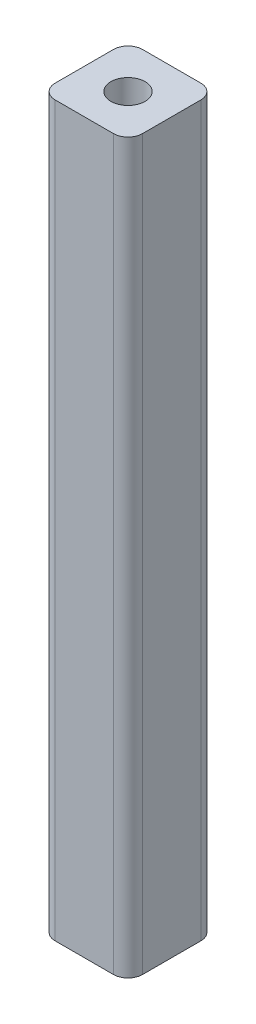
SolidWorks part; units mm, degrees
ref_plane "Front Plane" through (0, 0, 0) normal (0, 0, 1) x (1, 0, 0)
ref_plane "Top Plane" through (0, 0, 0) normal (0, 1, 0) x (1, 0, 0)
ref_plane "Right Plane" through (0, 0, 0) normal (1, 0, 0) x (0, 0, -1)
sketch "Sketch1" plane through (0, 0, 0) normal (0, 1, 0) x (1, 0, 0)
  line L0 (-6, 6) -> (6, -6) construction
  line L1 (-6, 6) -> (6, 6)
  line L2 (-6, 6) -> (-6, -6)
  line L3 (-6, -6) -> (6, -6)
  line L4 (6, 6) -> (6, -6)
  circle A0 centre (0, 0) radius 2.35
  point P7 (0, 0)
  dimension "D1" = 4.7
  dimension "D2" = 12
extrude "Boss-Extrude1" add sketch "Sketch1" along normal blind 100
fillet "Fillet1" radius 2 4 edges at (-6, 50, 6) (-6, 50, -6) (6, 50, -6) (6, 50, 6)
